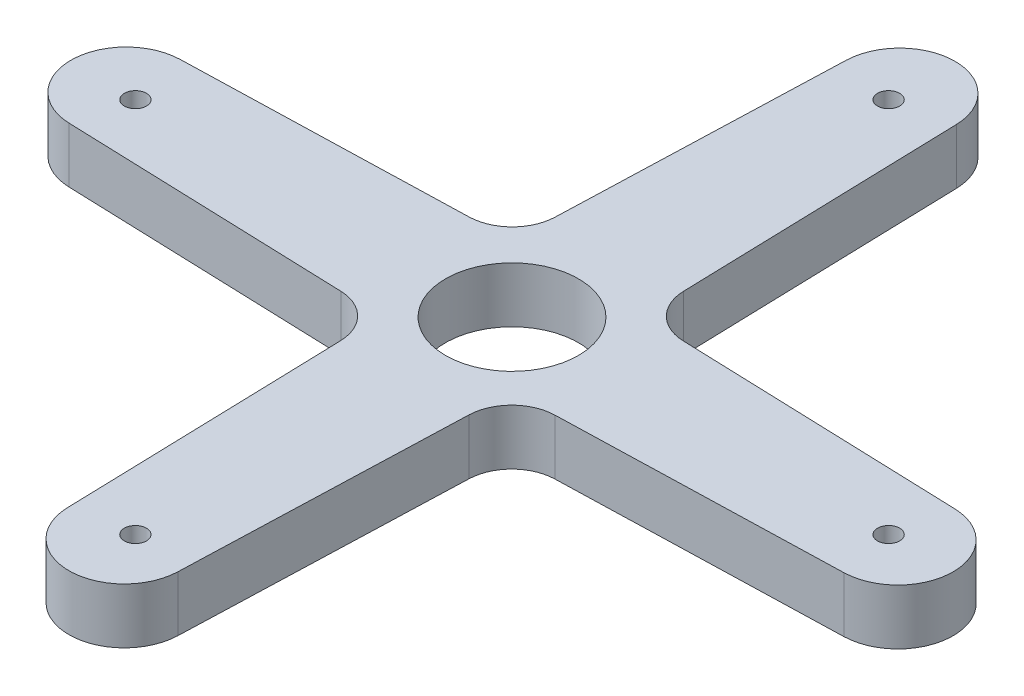
SolidWorks part; units mm, degrees
ref_plane "Front Plane" through (0, 0, 0) normal (0, 0, 1) x (1, 0, 0)
ref_plane "Top Plane" through (0, 0, 0) normal (0, 1, 0) x (1, 0, 0)
ref_plane "Right Plane" through (0, 0, 0) normal (1, 0, 0) x (0, 0, -1)
sketch "Sketch1" plane through (0, 0, 0) normal (0, 1, 0) x (1, 0, 0)
  line L0 (0, 0) -> (0, 20) construction
  line L1 (2.9155, 3) -> (2.499, 17.5714)
  line L2 (-3, 3) -> (-2.499, 17.5714)
  line L3 (2.9155, -2.9155) -> (17.4869, -2.499)
  line L4 (2.9155, 3) -> (17.4869, 2.499)
  line L5 (-3, -2.9155) -> (-2.5835, -17.4869)
  line L6 (2.9155, -2.9155) -> (2.4144, -17.4869)
  line L7 (-3, 3) -> (-17.5714, 2.5835)
  line L8 (-3, -2.9155) -> (-17.5714, -2.4144)
  line L10 (-3, 3) -> (2.9155, 3) construction
  line L11 (-3, 3) -> (-3, -2.9155) construction
  line L12 (-3, -2.9155) -> (2.9155, -2.9155) construction
  line L13 (2.9155, 3) -> (2.9155, -2.9155) construction
  circle A0 centre (0, 0) radius 3 construction
  arc A1 (2.499, 17.5714) -> (-2.499, 17.5714) centre (0, 17.5) ccw
  arc A2 (17.4869, -2.499) -> (17.4869, 2.499) centre (17.4155, 0) ccw
  arc A3 (-2.5835, -17.4869) -> (2.4144, -17.4869) centre (-0.0845, -17.4155) ccw
  arc A4 (-17.5714, 2.5835) -> (-17.5714, -2.4144) centre (-17.5, 0.0845) ccw
  point P5 (-19.8707, 4.7607)
  point P27 (-0.0423, 0.0423)
  dimension "D1" = 6
  dimension "D3" = 5
  dimension "D4" = 4
  dimension "D2" = 20
extrude "Boss-Extrude1" add sketch "Sketch1" along normal blind 2.5
fillet "Fillet1" radius 2 4 edges at (-3, 1.25, 2.9155) (2.9155, 1.25, 2.9155) (-3, 1.25, -3) (2.9155, 1.25, -3)
sketch "Sketch3" plane through (0, 2.5, 0) normal (0, 1, 0) x (1, 0, 0)
  line L0 (0, 20) -> (0, 17) construction
  line L1 (20, 0) -> (17, 0) construction
  line L2 (0, -20) -> (0, -17) construction
  line L3 (-20, 0) -> (-17, 0) construction
  arc A0 (2.499, 17.5714) -> (-2.499, 17.5714) centre (0, 17.5) ccw construction
  circle A1 centre (0, 17) radius 0.5
  circle A2 centre (17, 0) radius 0.5
  circle A3 centre (0, -17) radius 0.5
  circle A4 centre (-17, 0) radius 0.5
  circle A5 centre (0, 0) radius 3
  point P19 (0, 0)
  dimension "D2" = 1
  dimension "D4" = 6
  dimension "D1" = 3
  dimension "D3" = 4
extrude "Cut-Extrude1" cut sketch "Sketch3" against normal blind 2.5
